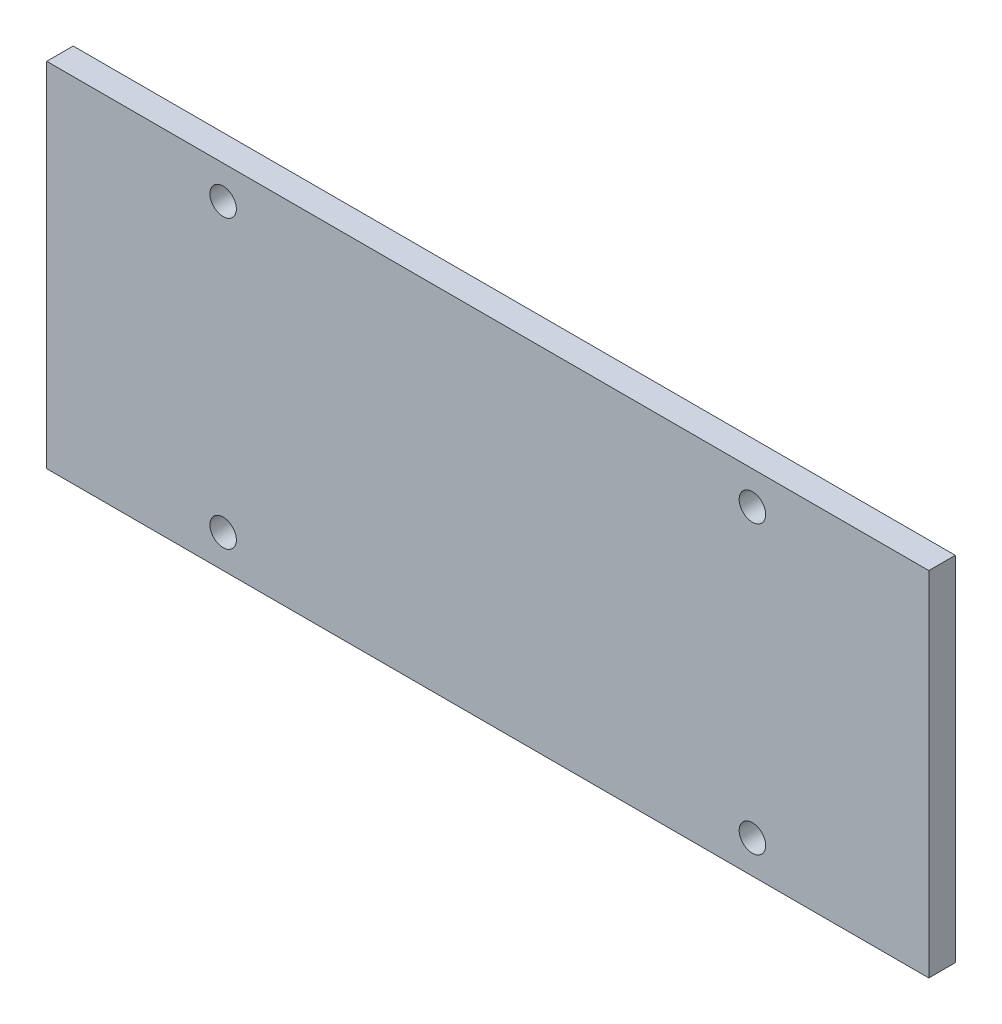
SolidWorks part; units mm, degrees
ref_plane "Front Plane" through (0, 0, 0) normal (0, 0, 1) x (1, 0, 0)
ref_plane "Top Plane" through (0, 0, 0) normal (0, 1, 0) x (1, 0, 0)
ref_plane "Right Plane" through (0, 0, 0) normal (1, 0, 0) x (0, 0, -1)
sketch "Sketch1" plane through (0, 0, 0) normal (0, 0, 1) x (1, 0, 0)
  line L1 (-50, 20) -> (50, 20)
  line L2 (-50, 20) -> (-50, -20)
  line L3 (-50, -20) -> (50, -20)
  line L4 (50, 20) -> (50, -20)
  line L5 (-50, 20) -> (50, -20) construction
  line L6 (-50, -20) -> (50, 20) construction
  circle A0 centre (-30, 16.25) radius 1.5
  circle A1 centre (30, 16.25) radius 1.5
  circle A2 centre (30, -16.25) radius 1.5
  circle A3 centre (-30, -16.25) radius 1.5
  point P0 (0, 0)
extrude "Boss-Extrude1" add sketch "Sketch1" along normal blind 3
